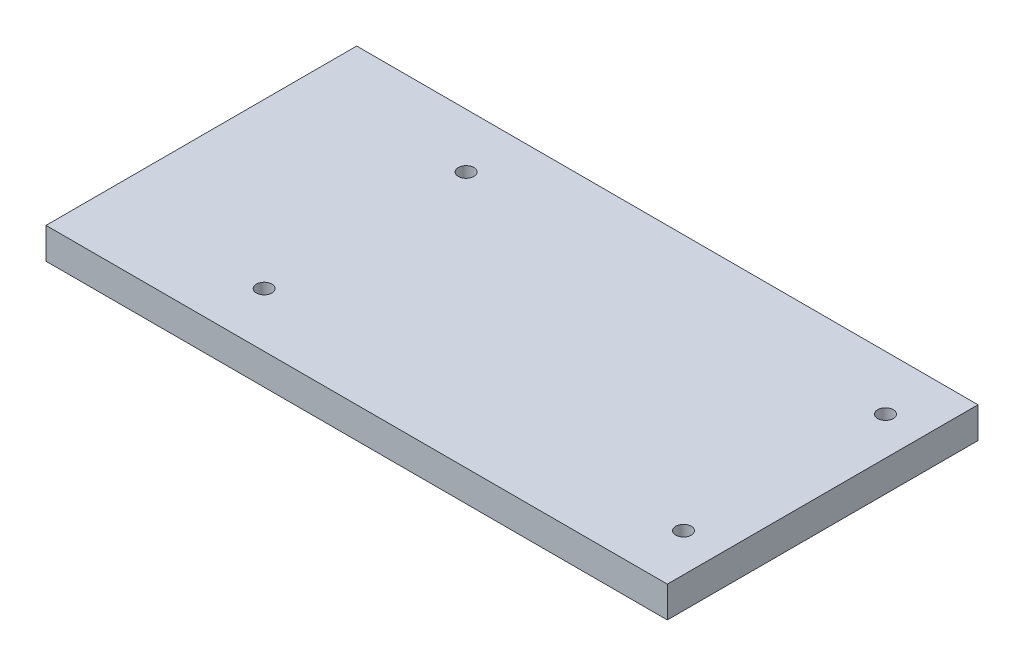
SolidWorks part; units mm, degrees
ref_plane "Front Plane" through (0, 0, 0) normal (0, 0, 1) x (1, 0, 0)
ref_plane "Top Plane" through (0, 0, 0) normal (0, 1, 0) x (1, 0, 0)
ref_plane "Right Plane" through (0, 0, 0) normal (1, 0, 0) x (0, 0, -1)
sketch "Sketch1" plane through (0, 0, 0) normal (0, 1, 0) x (1, 0, 0)
  line L1 (100, -50) -> (-100, -50)
  line L2 (100, -50) -> (100, 50)
  line L3 (100, 50) -> (-100, 50)
  line L4 (-100, -50) -> (-100, 50)
  line L5 (100, -50) -> (-100, 50) construction
  line L6 (100, 50) -> (-100, -50) construction
  point P0 (0, 0)
  dimension "D1" = 100
  dimension "D2" = 200
extrude "Boss-Extrude1" add sketch "Sketch1" along normal blind 10
sketch "Sketch2" plane through (0, 10, 0) normal (0, 1, 0) x (1, 0, 0)
  circle A0 centre (87.72, 32.5) radius 2.5
  circle A1 centre (-47.28, 32.5) radius 2.5
  circle A2 centre (-47.28, -32.5) radius 2.5
  circle A3 centre (87.72, -32.5) radius 2.5
extrude "Cut-Extrude1" cut sketch "Sketch2" against normal up to next
